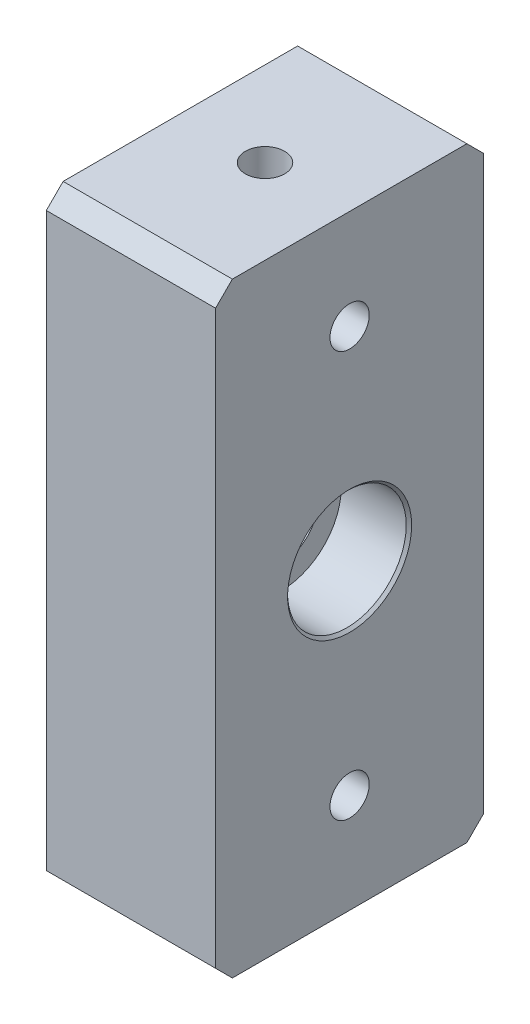
SolidWorks part; units mm, degrees
ref_plane "Front Plane" through (0, 0, 0) normal (0, 0, 1) x (1, 0, 0)
ref_plane "Top Plane" through (0, 0, 0) normal (0, 1, 0) x (1, 0, 0)
ref_plane "Right Plane" through (0, 0, 0) normal (1, 0, 0) x (0, 0, -1)
ref_plane "Plane1" through (15.875, 0, 0) normal (1, 0, 0) x (0, 0, -1)
sketch "Sketch1" plane through (15.875, 0, 0) normal (1, 0, 0) x (0, 0, -1)
  line L0 (-25.146, 57.15) -> (-25.146, 0.381)
  line L1 (-25.146, 0.381) -> (0, 0.381)
  line L2 (0, 0.381) -> (0, 57.15)
  line L3 (0, 57.15) -> (-25.146, 57.15)
extrude "Boss-Extrude1" add sketch "Sketch1" against normal blind 15.875
hole_wizard "Hole1" positions "Sketch3" profile "Sketch2" legacy
sketch "Sketch3" plane through (0, 0.381, 0) normal (0, -1, 0) x (-1, 0, 0)
  point P0 (-7.9375, -12.573)
sketch "Sketch2" plane through (7.9375, 0.381, 12.573) normal (1, 0, 0) x (0, 0, -1)
  line L0 (0, 0) -> (0, 13.8065)
  line L1 (0, 13.8065) -> (1.8415, 12.7)
  line L2 (1.8415, 12.7) -> (1.8415, 0)
  line L4 (1.8415, 0) -> (0, 0)
  line L6 (0, 13.8065) -> (-1.8415, 12.7) construction
  line L7 (0, -4.2442) -> (0, 117.3081) construction
  dimension "Diameter" = 3.683
  dimension "Depth" = 12.7
  dimension "Drill Angle" = 118
hole_wizard "Hole2" positions "Sketch5" profile "Sketch4" legacy
sketch "Sketch5" plane through (0, 57.15, 0) normal (0, 1, 0) x (1, 0, 0)
  point P0 (7.9375, -12.573)
sketch "Sketch4" plane through (7.9375, 57.15, 12.573) normal (1, 0, 0) x (0, 0, 1)
  line L0 (0, 0) -> (0, 13.8065)
  line L1 (0, 13.8065) -> (1.8415, 12.7)
  line L2 (1.8415, 12.7) -> (1.8415, 0)
  line L4 (1.8415, 0) -> (0, 0)
  line L6 (0, 13.8065) -> (-1.8415, 12.7) construction
  line L7 (0, -4.2442) -> (0, 117.3081) construction
  dimension "Diameter" = 3.683
  dimension "Depth" = 12.7
  dimension "Drill Angle" = 118
hole_wizard "Hole3" positions "Sketch7" profile "Sketch6" legacy
sketch "Sketch7" plane through (15.875, 0, 0) normal (1, 0, 0) x (0, 0, -1)
  point P0 (-12.573, 47.8155)
  point P1 (-12.573, 9.7155)
sketch "Sketch6" plane through (15.875, 47.8155, 12.573) normal (0, 1, 0) x (0, 0, -1)
  line L0 (0, 0) -> (0, 23.8125)
  line L1 (0, 23.8125) -> (1.8415, 23.8125)
  line L2 (1.8415, 23.8125) -> (1.8415, 0)
  line L3 (1.8415, 0) -> (0, 0)
  line L4 (0, 110) -> (0, -10) construction
  dimension "Diameter" = 3.683
  dimension "Depth" = 23.8125
hole_wizard "CBORE for M6 Hex Head Bolt1" positions "Sketch9" profile "Sketch8" counterbore size "M6" standard "ANSI Metric"
sketch "Sketch9" plane through (15.875, 0, 0) normal (1, 0, 0) x (0, 0, -1)
  point P0 (-12.573, 28.7655)
sketch "Sketch8" plane through (15.875, 28.7655, 12.573) normal (0, 1, 0) x (0, 0, -1)
  line L0 (0, 0) -> (0, 15.875)
  line L1 (0, 15.875) -> (3.3782, 15.875)
  line L3 (3.3782, 15.875) -> (3.3782, 6.35)
  line L4 (3.3782, 6.35) -> (5.5626, 6.35)
  line L5 (5.5626, 6.35) -> (5.5626, 0)
  line L7 (5.5626, 0) -> (0, 0)
  line L11 (0, -6.35) -> (0, 107.95) construction
  dimension "Thru Hole Dia." = 6.7564
  dimension "Thru Hole Depth" = 15.875
  dimension "C'Bore Dia." = 11.1252
  dimension "C'Bore Depth" = 6.35
chamfer "Chamfer1" distance 1.5748 angle 45 4 edges at (7.9375, 57.15, 25.146) (7.9375, 57.15, 0) (7.9375, 0.381, 0) (7.9375, 0.381, 25.146)
chamfer "Chamfer2" distance 0.254 angle 45 2 edges at (0, 28.7655, 9.1948) (15.875, 28.7655, 7.0104)
